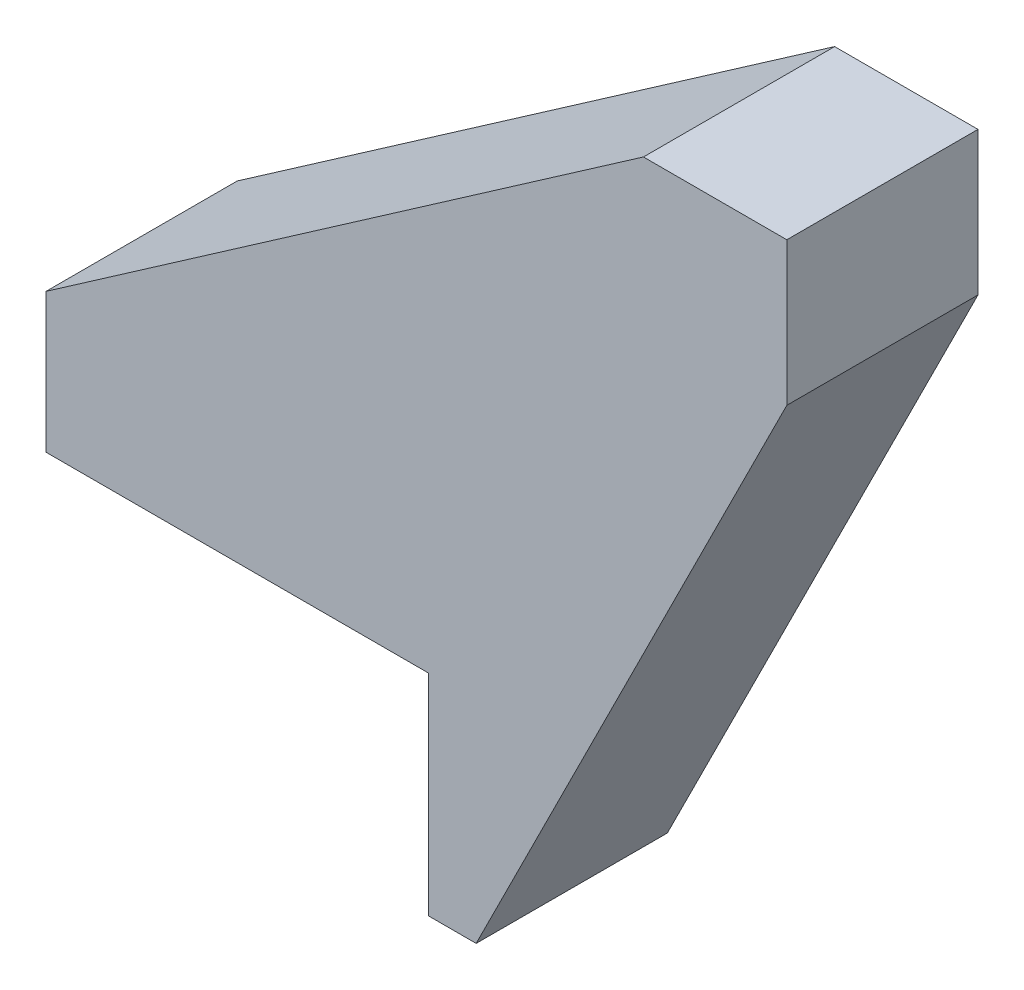
SolidWorks part; units mm, degrees
ref_plane "Front Plane" through (0, 0, 0) normal (0, 0, 1) x (1, 0, 0)
ref_plane "Top Plane" through (0, 0, 0) normal (0, 1, 0) x (1, 0, 0)
ref_plane "Right Plane" through (0, 0, 0) normal (1, 0, 0) x (0, 0, -1)
sketch "Sketch1" plane through (0, 0, 0) normal (0, 0, 1) x (1, 0, 0)
  line L0 (0, 0) -> (0, -13.97)
  line L1 (0, -13.97) -> (3.175, -13.97)
  line L2 (3.175, -13.97) -> (23.8118, 27.305)
  line L3 (23.8118, 27.305) -> (23.8118, 36.83)
  line L4 (23.8118, 36.83) -> (14.2868, 36.83)
  line L5 (14.2868, 36.83) -> (-25.4, 9.2548)
  line L6 (-25.4, 9.2548) -> (-25.4, 0)
  line L7 (-25.4, 0) -> (0, 0)
  dimension "D1" = 25.4
  dimension "D2" = 13.97
  dimension "D3" = 3.175
  dimension "D4" = 9.525
  dimension "D5" = 9.525
  dimension "D6" = 50.8
extrude "Boss-Extrude1" add sketch "Sketch1" along normal blind 12.7
